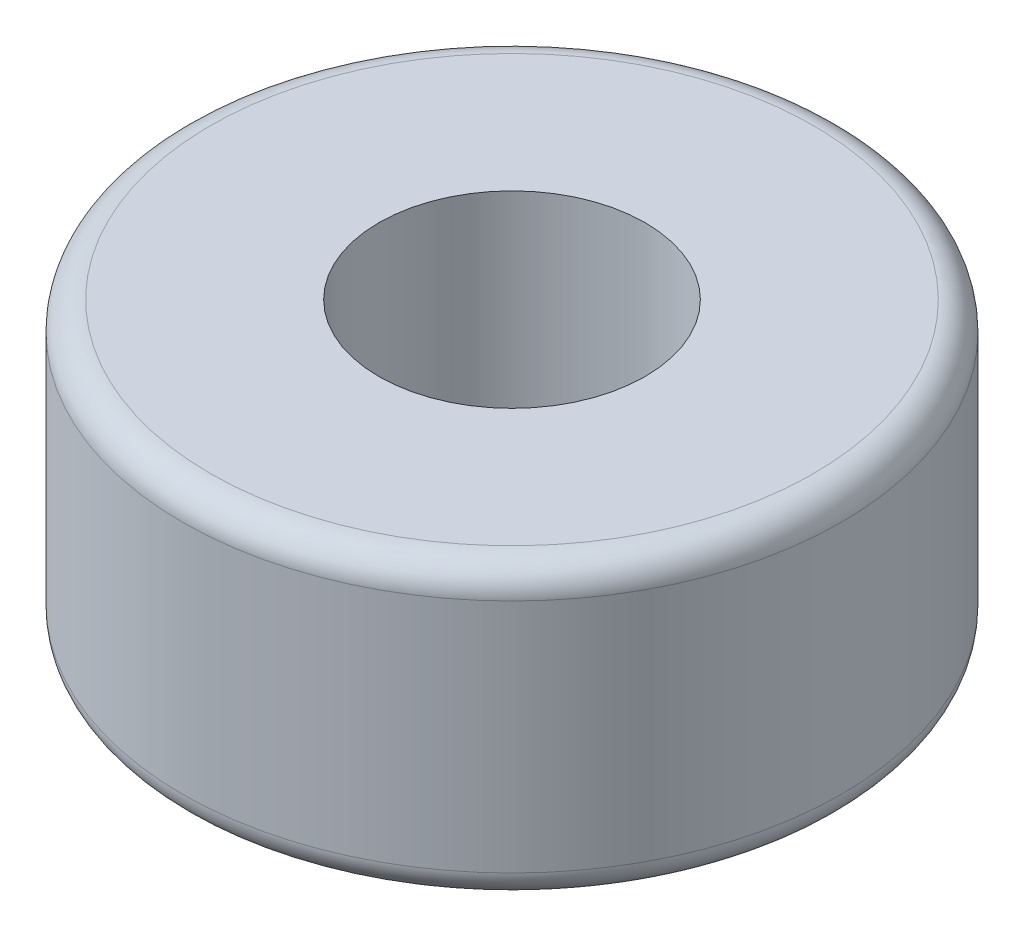
SolidWorks part; units mm, degrees
ref_plane "Front" through (0, 0, 0) normal (0, 0, 1) x (1, 0, 0)
ref_plane "Top" through (0, 0, 0) normal (0, 1, 0) x (1, 0, 0)
ref_plane "Right" through (0, 0, 0) normal (1, 0, 0) x (0, 0, -1)
sketch "Sketch1" plane through (0, 0, 0) normal (0, 1, 0) x (1, 0, 0)
  circle A0 centre (0, 0) radius 5.875
  circle A1 centre (0, 0) radius 2.375
  dimension "D1" = 11.75
  dimension "D2" = 4.75
extrude "Boss-Extrude1" add sketch "Sketch1" along normal blind 5.2
fillet "Fillet1" radius 0.5 2 edges at (0, 0, 5.875) (0, 5.2, 5.875)
